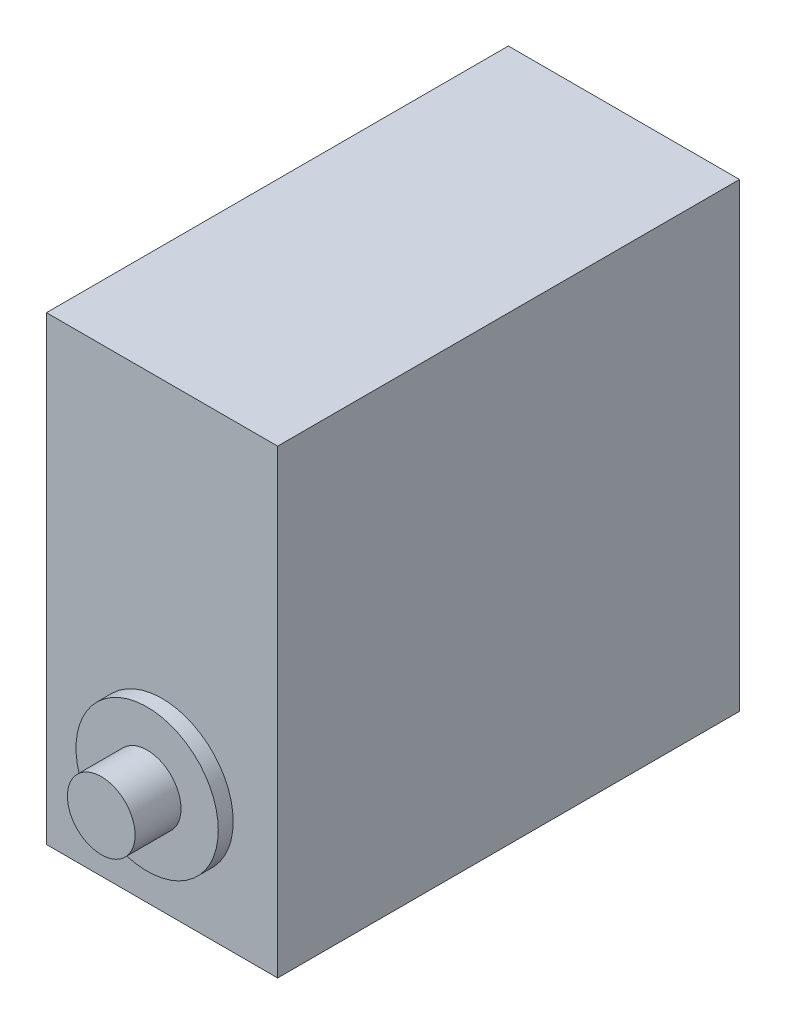
SolidWorks part; units mm, degrees
ref_plane "Front Plane" through (0, 0, 0) normal (1, 0, 0) x (0, 1, 0)
ref_plane "Top Plane" through (0, 0, 0) normal (0, 0, 1) x (0, 1, 0)
ref_plane "Right Plane" through (0, 0, 0) normal (0, 1, 0) x (-1, 0, 0)
sketch "Sketch1" plane through (0, 0, 0) normal (0, 0, 1) x (0, 1, 0)
  line L1 (-20.075, -10.075) -> (20.075, -10.075)
  line L2 (-20.075, -10.075) -> (-20.075, 10.075)
  line L3 (-20.075, 10.075) -> (20.075, 10.075)
  line L4 (20.075, -10.075) -> (20.075, 10.075)
  line L5 (-20.075, -10.075) -> (20.075, 10.075) construction
  line L6 (-20.075, 10.075) -> (20.075, -10.075) construction
  point P0 (0, 0)
  dimension "D1" = 40.15
  dimension "D2" = 20.15
extrude "Boss-Extrude1" add sketch "Sketch1" along normal mid plane 40.26
sketch "Sketch2" plane through (0, 0, 20.13) normal (0, 0, 1) x (1, 0, 0)
  line L1 (-10.075, -20.075) -> (10.075, -20.075) construction
  circle A0 centre (0, -10.205) radius 6.2
  dimension "D1" = 12.4
  dimension "D2" = 3.67
extrude "Boss-Extrude2" add sketch "Sketch2" along normal blind 1.3
mirror "Mirror1" about plane through (0, 0, 0) normal (0, 0, 1) of "Boss-Extrude2"
sketch "Sketch3" plane through (0, 0, -21.43) normal (0, 0, -1) x (1, 0, 0)
  circle A0 centre (0, 10.205) radius 3
  dimension "D1" = 6
extrude "Boss-Extrude3" add sketch "Sketch3" along normal blind 4
sketch "Sketch7" plane through (0, 0, 21.43) normal (0, 0, 1) x (1, 0, 0)
  circle A0 centre (0, -10.205) radius 2.95
  dimension "D1" = 5.9
extrude "Boss-Extrude4" add sketch "Sketch7" along normal blind 4
